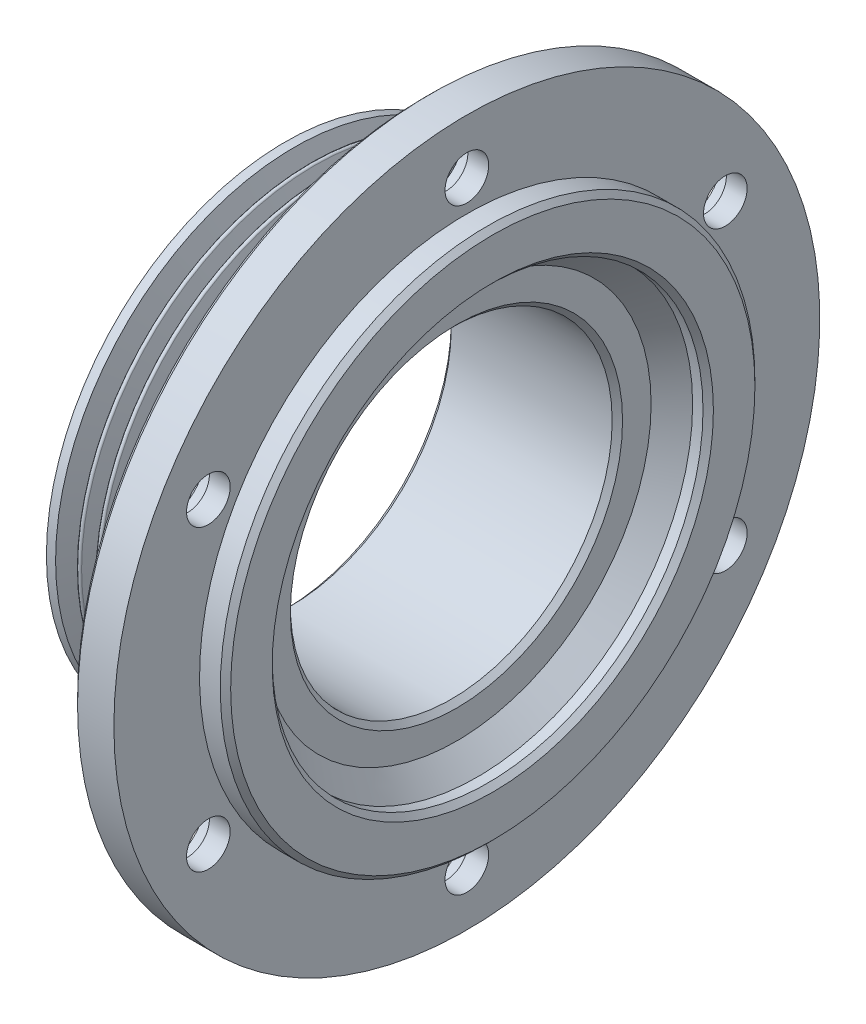
SolidWorks part; units mm, degrees
material "3.0205 (EN-AW 1200)"
ref_plane "Спереди" through (0, 0, 0) normal (0, 0, 1) x (1, 0, 0)
ref_plane "Сверху" through (0, 0, 0) normal (0, 1, 0) x (1, 0, 0)
ref_plane "Справа" through (0, 0, 0) normal (1, 0, 0) x (0, 0, -1)
sketch "Эскиз1" plane through (0, 0, 0) normal (0, 0, 1) x (1, 0, 0)
  line L0 (0, 0) -> (50000, 0) construction
  line L1 (-13.5, 31) -> (-13.5, 46) construction
  line L2 (-13.5, 46) -> (13.5, 46)
  line L5 (0, 0) -> (0, 50000) construction
  line L7 (13.5, 46) -> (13.5, 68)
  line L8 (13.5, 68) -> (21.5, 68)
  line L9 (21.5, 68) -> (21.5, 31)
  line L11 (-13.5, 31) -> (21.5, 31)
  line L13 (-0.0928, 46) -> (13.5, 46) construction
  line L26 (-13.5, 46) -> (-13.5, 31)
  dimension "D6" = 136
  dimension "D1" = 92
  dimension "D2" = 62
  dimension "D3" = 27
  dimension "D5" = 8
revolve "Повернуть1" add sketch "Эскиз1" angle 360 about L0
sketch "Эскиз2" plane through (0, 0, 0) normal (0, 0, 1) x (1, 0, 0)
  line L0 (0, 0) -> (-50000, 0) construction
  line L1 (-9.94, 41.6806) -> (-9.94, -49958.3194) construction
  line L2 (-11.7321, 46) -> (-9.94, 41.0762)
  line L3 (13.5, 46) -> (-13.5, 46) construction
  line L4 (-9.94, 41.0762) -> (-8.1479, 46)
  line L5 (-8.1479, 46) -> (-11.7321, 46)
  line L6 (-13.5, 46) -> (-13.5, -46) construction
  line L7 (-9.6745, 45) -> (49990.3255, 45) construction
  line L8 (13.5, 46) -> (-13.5, 46) construction
  circle A0 centre (-9.94, 44) radius 1 construction
  dimension "D3" = 2
  dimension "D1" = 40
  dimension "D2" = 3.56
  dimension "D4" = 1
revolve "Вырез-Повернуть1" cut sketch "Эскиз2" angle 360 about L0
pattern_linear "Линейный массив1" count 5 spacing 3.56 along (1, 0, 0) of "Вырез-Повернуть1"
sketch "Эскиз6" plane through (13.5, 0, 0) normal (-1, 0, 0) x (0, 0, 1)
  circle A0 centre (0, 0) radius 57.5
  point P0 (0, 57.5)
hole_wizard "Цековка для винта с внутренним шестигранником M81" positions "Эскиз6" profile "Эскиз5" counterbore size "M8" standard "DIN" end condition through all
sketch "Эскиз5" plane through (13.5, 57.5, 0) normal (0, 1, 0) x (0, 0, 1)
  line L0 (0, 0) -> (0, 8)
  line L1 (0, 8) -> (4.2, 8)
  line L3 (4.2, 8) -> (4.2, 4)
  line L4 (4.2, 4) -> (7.5, 4)
  line L5 (7.5, 4) -> (7.5, 0)
  line L7 (7.5, 0) -> (0, 0)
  line L11 (0, -6.35) -> (0, 107.95) construction
  dimension "Диаметр сквозного отверстия" = 8.4
  dimension "Глубина сквозного отверстия" = 8
  dimension "Диаметр цековки" = 15
  dimension "Глубина цековки" = 4
pattern_circular "Круговой массив1" count 6 over 360 about axis through (0, 0, 0) along (1, 0, 0) of "Цековка для винта с внутренним шестигранником M81"
sketch "Эскиз7" plane through (21.5, 0, 0) normal (1, 0, 0) x (0, 0, -1)
  circle A0 centre (0, 0) radius 41.5
  dimension "D1" = 83
extrude "Вырез-Вытянуть2" cut sketch "Эскиз7" against normal blind 2 contours A0
fillet "Скругление1" radius 0.4 5 edges at (4.3, 0, -41.0762) (0.74, 0, -41.0762) (-2.82, 0, -41.0762) (-6.38, 0, -41.0762) (-9.94, 0, -41.0762)
sketch "Эскиз8" plane through (0, 0, 0) normal (0, 0, 1) x (1, 0, 0)
  line L0 (21.5, 41.5) -> (21.5, 51.5)
  line L1 (21.5, 51.5) -> (26.5, 51.5)
  line L2 (26.5, 51.5) -> (26.5, 41.5)
  line L3 (26.5, 41.5) -> (21.5, 41.5)
  line L4 (21.5, -41.5) -> (21.5, 41.5) construction
  line L5 (0, 0) -> (50000, 0) construction
  dimension "D1" = 83
  dimension "D2" = 10
  dimension "D3" = 5
revolve "Повернуть2" add sketch "Эскиз8" angle 360 about L5
chamfer "Фаска1" distance 4 angle 45 1 edges at (19.5, 0, -41.5)
chamfer "Фаска2" distance 1 angle 45 1 edges at (26.5, -51.5, 0)
chamfer "Фаска3" distance 1 angle 45 1 edges at (13.5, 0, 68)
chamfer "Фаска4" distance 1 angle 45 3 edges at (19.5, 0, -31) (-13.5, 0, 31) (26.5, -41.5, 0)
fillet "Скругление5" radius 2 1 edges at (13.5, 0, 46)
fillet "Скругление6" radius 0.4 4 edges at (2.52, 0, 45.9667) (-1.04, 0, 45.9667) (-4.6, 0, 45.9667) (-8.16, 0, 45.9667)
